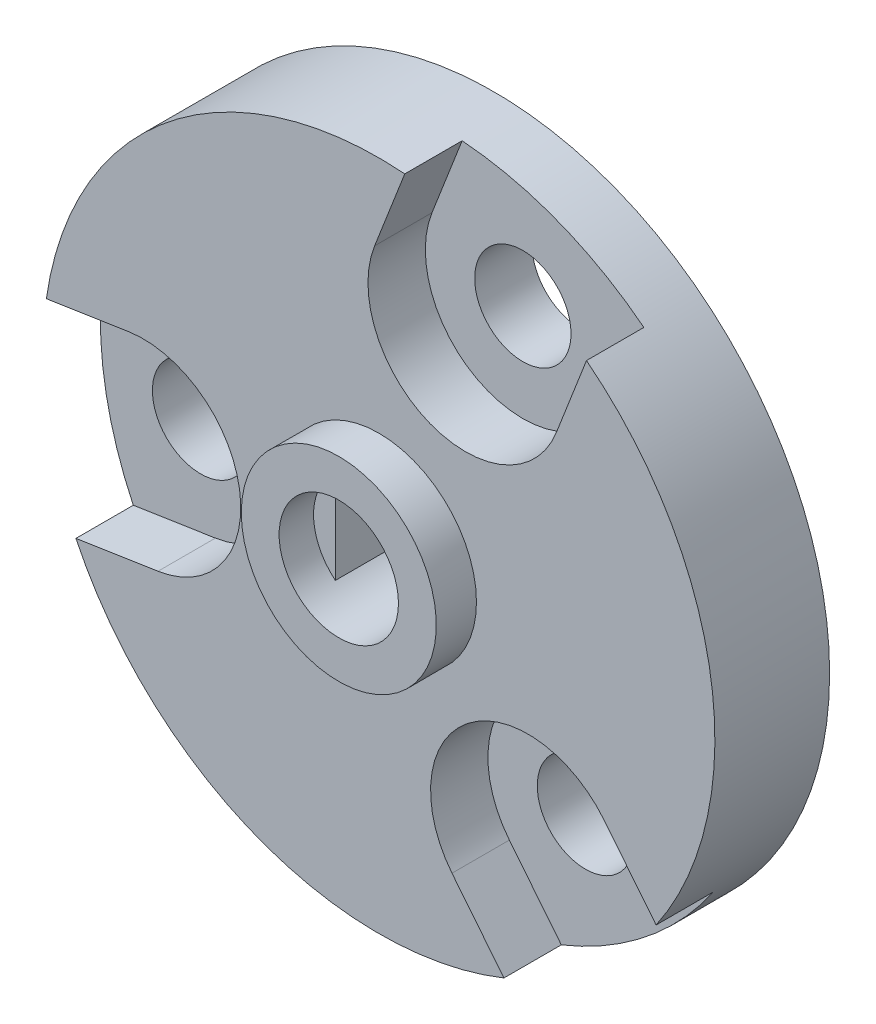
SolidWorks part; units mm, degrees
ref_plane "Front Plane" through (0, 0, 0) normal (0, 0, 1) x (1, 0, 0)
ref_plane "Top Plane" through (0, 0, 0) normal (0, 1, 0) x (1, 0, 0)
ref_plane "Right Plane" through (0, 0, 0) normal (1, 0, 0) x (0, 0, -1)
sketch "Sketch1" plane through (0, 0, 0) normal (0, 0, 1) x (1, 0, 0)
  circle A0 centre (0, 0) radius 14.6423
  circle A1 centre (3.7722, 9.6835) radius 4.25 construction
extrude "Boss-Extrude1" add sketch "Sketch1" along normal blind 2.5
ref_plane "Plane1" through (0, 0, 2.5) normal (0, 0, 1) x (1, 0, 0)
sketch "Sketch2" plane through (0, 0, 2.5) normal (0, 0, 1) x (1, 0, 0)
  line L0 (9.0462, 11.5136) -> (7.7323, 8.1409)
  line L1 (1.1259, 14.599) -> (-0.1879, 11.2262)
  line L2 (-10.9164, 2.626) -> (-14.4942, 2.0774)
  line L3 (-9.6282, -5.7759) -> (-13.206, -6.3244)
  line L4 (12.0801, -8.2745) -> (9.8161, -5.4503)
  line L5 (5.448, -13.591) -> (3.184, -10.7668)
  arc A1 (1.1259, 14.599) -> (-14.4942, 2.0774) centre (0, 0) ccw
  circle A2 centre (0, 0) radius 14.6423 construction
  arc A3 (-0.1879, 11.2262) -> (7.7323, 8.1409) centre (3.7722, 9.6835) ccw
  arc A4 (-9.6282, -5.7759) -> (-10.9164, 2.626) centre (-10.2723, -1.5749) ccw
  arc A6 (9.8161, -5.4503) -> (3.184, -10.7668) centre (6.5001, -8.1086) ccw
  arc A8 (12.0801, -8.2745) -> (9.0462, 11.5136) centre (0, 0) ccw
  arc A9 (-13.206, -6.3244) -> (5.448, -13.591) centre (0, 0) ccw
  circle A10 centre (0, 0) radius 14.6423 construction
  circle A13 centre (6.5001, -8.1086) radius 4.25 construction
  circle A14 centre (-10.2723, -1.5749) radius 4.25 construction
  circle A15 centre (3.7722, 9.6835) radius 4.25 construction
extrude "Boss-Extrude2" add sketch "Sketch2" along normal blind 2.5
sketch "Sketch4" plane through (0, 0, 2.5) normal (0, 0, 1) x (1, 0, 0)
  circle A0 centre (3.7722, 9.6835) radius 2.1
  circle A1 centre (-10.2723, -1.5749) radius 2.1
  circle A3 centre (6.5001, -8.1086) radius 2.1
  dimension "D1" = 4.2
ref_plane "Plane2" through (0, 0, 5) normal (0, 0, 1) x (1, 0, 0)
sketch "Sketch3" plane through (0, 0, 5) normal (0, 0, 1) x (1, 0, 0)
  circle A0 centre (0, 0) radius 4.25
  circle A3 centre (0, 0) radius 4.25 construction
extrude "Boss-Extrude3" add sketch "Sketch3" along normal offset from surface (1.75 mm away) 0.5
extrude "Cut-Extrude1" cut sketch "Sketch4" against normal through all
ref_plane "Plane3" through (0, 0, 6.75) normal (0, 0, 1) x (1, 0, 0)
sketch "Sketch5" plane through (0, 0, 6.75) normal (0, 0, 1) x (1, 0, 0)
  circle A0 centre (0, 0) radius 2.6
  dimension "D1" = 5.2
extrude "Cut-Extrude2" cut sketch "Sketch5" against normal blind 1.5
sketch "Sketch6" plane through (0, 0, 6.75) normal (0, 0, 1) x (1, 0, 0)
  line L0 (-1.65, 2.0094) -> (-1.65, -2.0094)
  line L1 (1.65, -2.0094) -> (1.65, 2.0094)
  arc A0 (1.65, 2.0094) -> (-1.65, 2.0094) centre (0, 0) ccw
  arc A1 (-1.65, -2.0094) -> (1.65, -2.0094) centre (0, 0) ccw
  circle A2 centre (0, 0) radius 2.6 construction
  dimension "D1" = 3.3
extrude "Cut-Extrude3" cut sketch "Sketch6" against normal up to next
